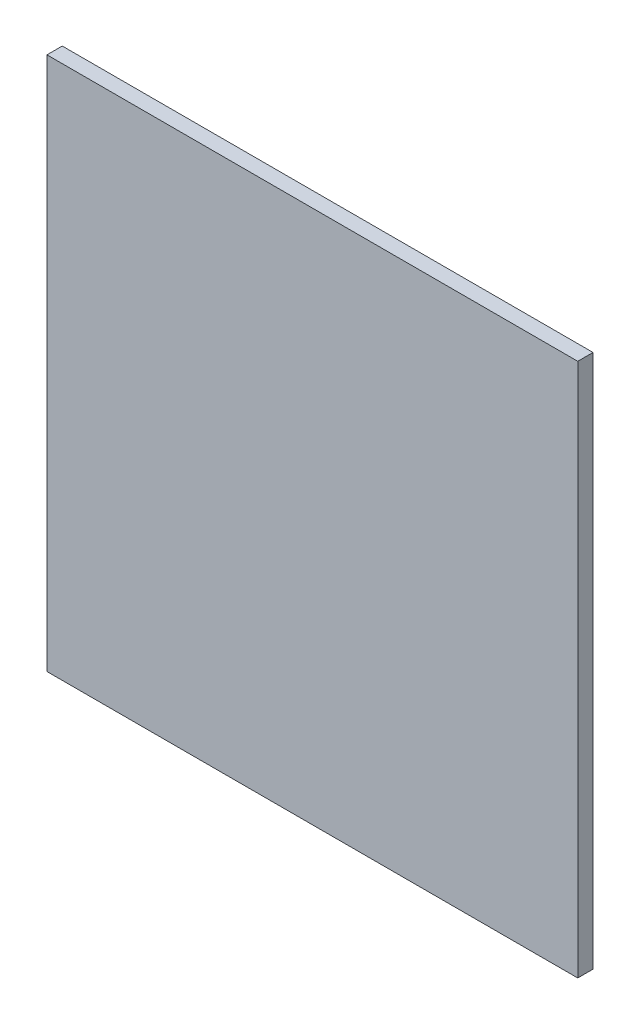
SolidWorks part; units mm, degrees
ref_plane "Front Plane" through (0, 0, 0) normal (0, 0, 1) x (1, 0, 0)
ref_plane "Top Plane" through (0, 0, 0) normal (0, 1, 0) x (1, 0, 0)
ref_plane "Right Plane" through (0, 0, 0) normal (1, 0, 0) x (0, 0, -1)
sketch "Sketch1" plane through (0, 0, 0) normal (0, 0, 1) x (1, 0, 0)
  line L1 (0, 0) -> (88.2133, 0)
  line L2 (0, 0) -> (0, 88.7639)
  line L3 (0, 88.7639) -> (88.2133, 88.7639)
  line L4 (88.2133, 0) -> (88.2133, 88.7639)
extrude "Boss-Extrude1" add sketch "Sketch1" along normal blind 2.54
surface "Surface-Flatten1"
